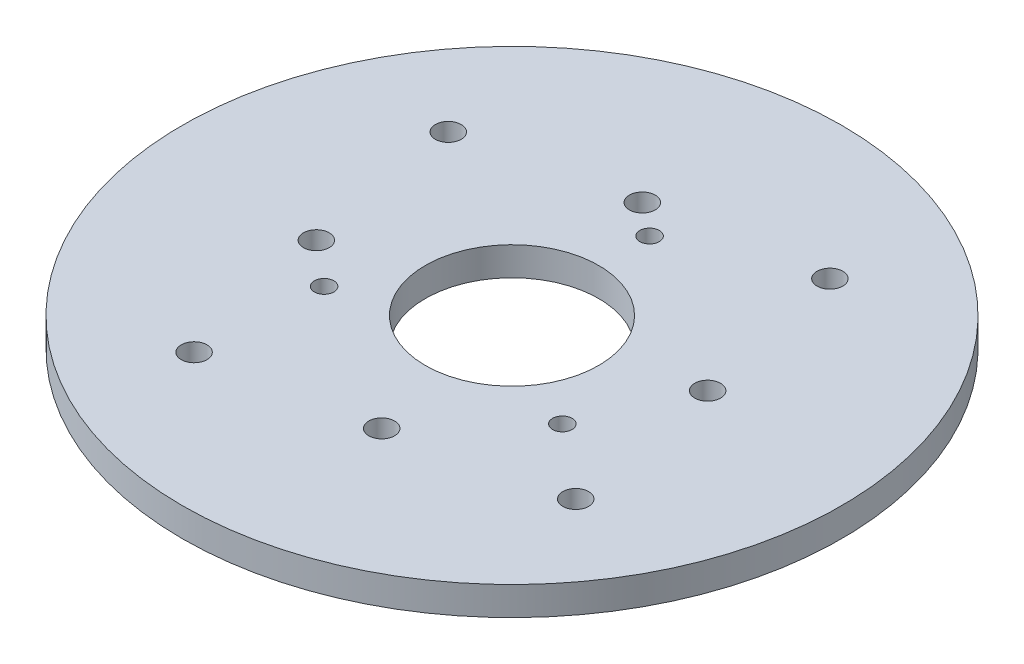
SolidWorks part; units mm, degrees
material "6061-T6 (SS)"
ref_plane "Front Plane" through (0, 0, 0) normal (0, 0, 1) x (1, 0, 0)
ref_plane "Top Plane" through (0, 0, 0) normal (0, 1, 0) x (1, 0, 0)
ref_plane "Right Plane" through (0, 0, 0) normal (1, 0, 0) x (0, 0, -1)
sketch "Sketch1" plane through (0, 0, 0) normal (0, 1, 0) x (1, 0, 0)
  line L0 (0, 0) -> (14.7397, -73.5373) construction
  line L1 (0, 0) -> (47.8563, -31.8751) construction
  circle A0 centre (0, 0) radius 57.5
  circle A1 centre (0, 0) radius 15.125
  circle A2 centre (0, 0) radius 29 construction
  circle A3 centre (0, 0) radius 40 construction
  circle A4 centre (5.6993, -28.4344) radius 2.25
  circle A5 centre (33.2914, -22.174) radius 2.25
  circle A6 centre (-28.4344, -5.6993) radius 2.25
  circle A7 centre (-22.174, -33.2914) radius 2.25
  circle A8 centre (0, 0) radius 29 construction
  circle A9 centre (-5.6993, 28.4344) radius 2.25
  circle A10 centre (-33.2914, 22.174) radius 2.25
  circle A11 centre (0, 0) radius 29 construction
  circle A12 centre (28.4344, 5.6993) radius 2.25
  circle A13 centre (22.174, 33.2914) radius 2.25
  circle A14 centre (0, 0) radius 29 construction
  point P30 (0, 0)
  dimension "D1" = 115
  dimension "D2" = 30.25
  dimension "D3" = 58
  dimension "D4" = 80
  dimension "D5" = 4.5
  dimension "D7" = 4.5
  dimension "D6" = 45
  dimension "D8" = 4
extrude "Boss-Extrude1" add sketch "Sketch1" along normal blind 5
sketch "Sketch3" plane through (0, 5, 0) normal (0, 1, 0) x (1, 0, 0)
  circle A2 centre (0, 0) radius 24 construction
  circle A3 centre (0, 24) radius 1.7
  circle A4 centre (0, 0) radius 24 construction
  circle A6 centre (0, 0) radius 24 construction
  circle A8 centre (0, 0) radius 24 construction
  circle A9 centre (24, 0) radius 1.7 [skipped]
  circle A10 centre (-24, 0) radius 1.7 [skipped]
  circle A11 centre (0, -24) radius 1.7 [skipped]
  circle A12 centre (20.7846, -12) radius 1.7
  circle A13 centre (0, 0) radius 24 construction
  circle A14 centre (-20.7846, -12) radius 1.7
  circle A15 centre (0, 0) radius 24 construction
  point P16 (0, 0)
  point P17 (0, 0)
  dimension "D1" = 48
  dimension "D3" = 3.4
  dimension "D2" = 4
  dimension "D4" = 3
extrude "Cut-Extrude1" cut sketch "Sketch3" against normal through all
equation "\"D1@Sketch1\"=\"UTL_DeckOD\""
equation "\"D2@Sketch1\"=\"UTL_CentralClearDia\""
equation "\"D3@Sketch1\"=\"UTL_SupportBCDia\""
equation "\"D4@Sketch1\"=\"UTL_MainTowerMountBCD\""
equation "\"D5@Sketch1\"=\"UTL_SupportHoleClearDia\""
equation "\"D7@Sketch1\"=\"UTL_MainTowerMountHoleClearDia\""
equation "\"D1@Boss-Extrude1\"=\"UTL_DeckThk\""
equation "\"____ GENERATED PART EXPORTS ____\" = 0"
equation "\"SYS_VersionTag\" = 2"
equation "\"UTL_DeckOD\" = 115mm"
equation "\"UTL_DeckThk\" = 5mm"
equation "\"UTL_CentralClearDia\" = 30.25mm"
equation "\"UTL_SupportBCDia\" = 58mm"
equation "\"UTL_SupportHoleClearDia\" = 4.5mm"
equation "\"UTL_MainTowerMountBCD\" = 80mm"
equation "\"UTL_MainTowerMountHoleClearDia\" = 4.5mm"
equation "\"UTL_MainTowerMountHoleCount\" = 4"
equation "\"CTRL_MainTowerOD\" = 8mm"
equation "\"LDG_MountBCDia\" = 48mm"
equation "\"LDG_MountClearDia\" = 3.4mm"
equation "\"LDG_MountCount\" = 3"
equation "\"D1@Sketch3\"=\"LDG_MountBCDia\""
equation "\"D3@Sketch3\"=\"LDG_MountClearDia\""
